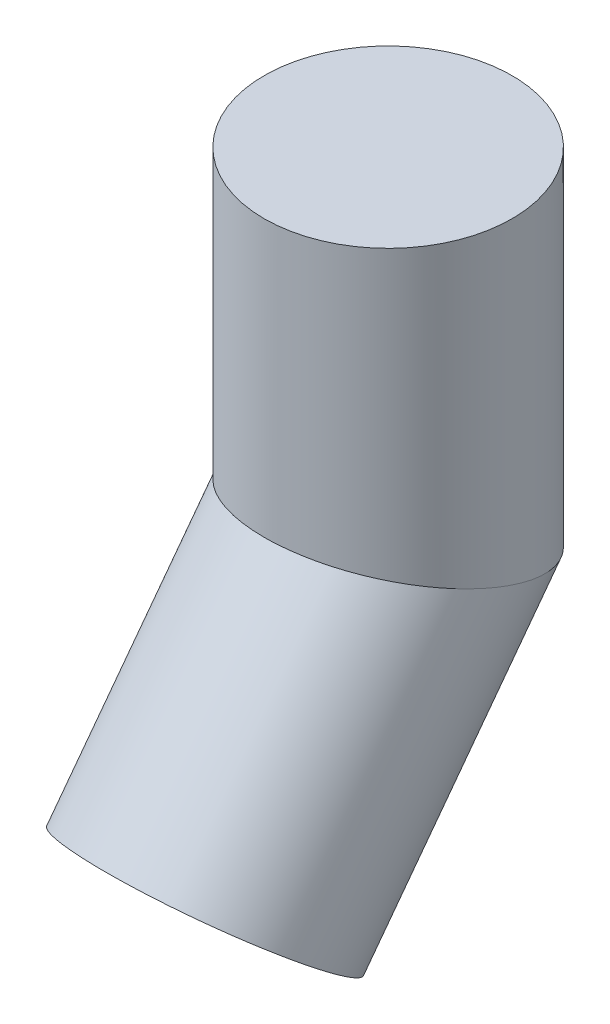
SolidWorks part; units mm, degrees
ref_plane "Alzado" through (0, 0, 0) normal (0, 0, 1) x (1, 0, 0)
ref_plane "Planta" through (0, 0, 0) normal (0, 1, 0) x (1, 0, 0)
ref_plane "Vista lateral" through (0, 0, 0) normal (1, 0, 0) x (0, 0, -1)
sketch "Croquis1" plane through (0, 0, 0) normal (0, 1, 0) x (1, 0, 0)
  circle A0 centre (0, 0) radius 101.6
  dimension "D1" = 203.2
extrude "Saliente-Extruir1" add sketch "Croquis1" against normal blind 10
sketch3d "Croquis3D1"
  line L0 (0, -10, 0) -> (0, -260, 0)
  line L1 (0, -10, 0) -> (0, 0, 0) construction
  line L2 (0, -260, 0) -> (0, -460, 0) construction
  line L3 (0, -460, 0) -> (0, -460, 150) construction
  line L4 (0, -460, 150) -> (0, -260, 0)
  dimension "D1" = 250
  dimension "D2" = 200
  dimension "D3" = 150
sketch "Croquis2" plane through (0, -10, 0) normal (0, -1, 0) x (1, 0, 0)
  circle A0 centre (0, 0) radius 101.6
sweep "Barrer1" add profiles "Croquis2" path "Croquis3D1"
